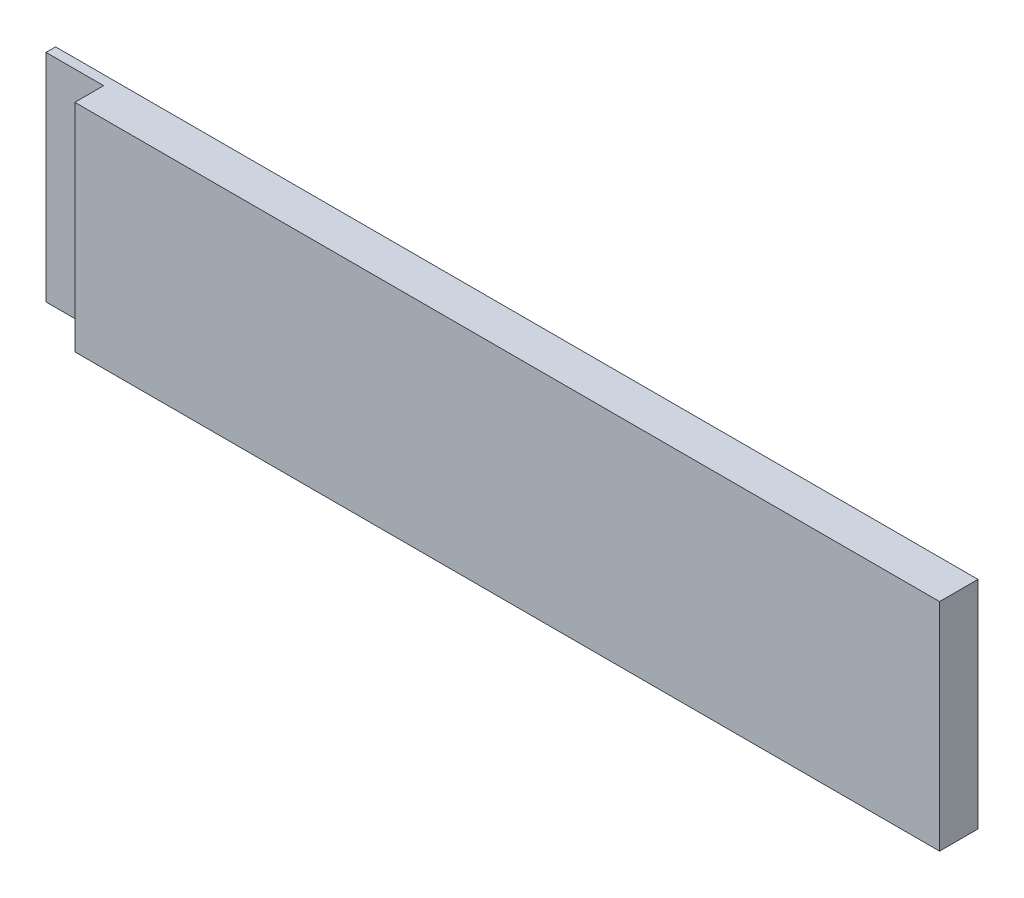
SolidWorks part; units mm, degrees
ref_plane "Front Plane" through (0, 0, 0) normal (0, 0, 1) x (1, 0, 0)
ref_plane "Top Plane" through (0, 0, 0) normal (0, 1, 0) x (1, 0, 0)
ref_plane "Right Plane" through (0, 0, 0) normal (1, 0, 0) x (0, 0, -1)
sketch "Sketch1" plane through (0, 0, 0) normal (0, 0, 1) x (1, 0, 0)
  line L1 (-152.4, -35.7124) -> (152.4, -35.7124)
  line L2 (-152.4, -35.7124) -> (-152.4, 35.7124)
  line L3 (-152.4, 35.7124) -> (152.4, 35.7124)
  line L4 (152.4, -35.7124) -> (152.4, 35.7124)
  line L5 (-152.4, -35.7124) -> (152.4, 35.7124) construction
  line L6 (-152.4, 35.7124) -> (152.4, -35.7124) construction
  point P0 (0, 0)
  dimension "D1" = 304.8
  dimension "D2" = 71.4248
extrude "Boss-Extrude1" add sketch "Sketch1" along normal blind 12.7 contours L3 L4 L1 L2
sketch "Sketch2" plane through (0, 0, 12.7) normal (0, 0, 1) x (1, 0, 0)
  line L1 (-152.4, 35.7124) -> (-133.35, 35.7124)
  line L2 (-152.4, 35.7124) -> (-152.4, -35.7124)
  line L3 (-152.4, -35.7124) -> (-133.35, -35.7124)
  line L4 (-133.35, 35.7124) -> (-133.35, -35.7124)
  dimension "D1" = 19.05
extrude "Cut-Extrude1" cut sketch "Sketch2" against normal blind 9.525 contours L4 L3 L2 L1
